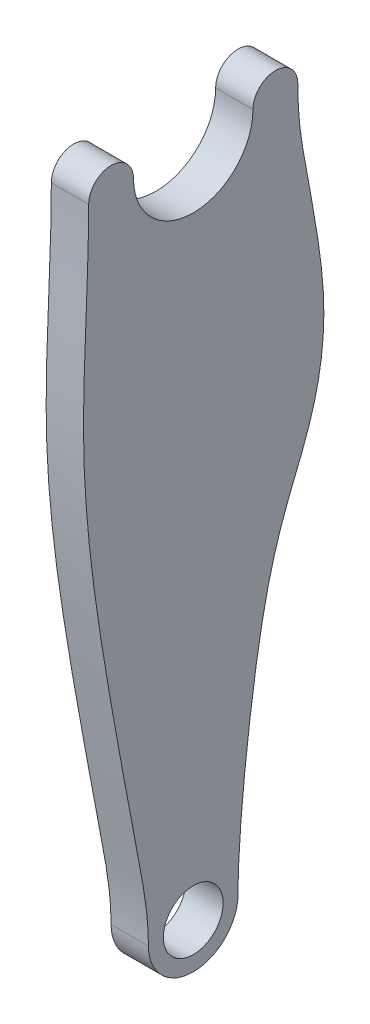
SolidWorks part; units mm, degrees
ref_plane "Front Plane" through (0, 0, 0) normal (0, 0, 1) x (1, 0, 0)
ref_plane "Top Plane" through (0, 0, 0) normal (0, 1, 0) x (1, 0, 0)
ref_plane "Right Plane" through (0, 0, 0) normal (1, 0, 0) x (0, 0, -1)
sketch "Sketch1" plane through (0, 0, 0) normal (1, 0, 0) x (0, 0, -1)
  line L0 (0, 0) -> (0, -180) construction
  line L1 (-22, 0) -> (0, 0) construction
  line L2 (0, 0) -> (22, 0) construction
  line L3 (-12, -180) -> (12, -180) construction
  line L4 (-28, 0) -> (-22, 0) construction
  line L5 (22, 0) -> (28, 0) construction
  arc A1 (-16, 0) -> (-28, 0) centre (-22, 0) ccw
  circle A2 centre (0, -180) radius 8
  arc A3 (12, -180) -> (-12, -180) centre (0, -180) cw
  arc A4 (-16, 0) -> (16, 0) centre (0, 0) ccw
  arc A5 (16, 0) -> (28, 0) centre (22, 0) cw
  spline S0 degree 3 poles (-28, 0) (-28, -19.8415) (-31.4918, -55.9451) (-24.0979, -109.0865) (-16.3697, -149.4261) (-12, -172.5449) (-12, -180) knots 0 0 0 0 0.318522 0.61075 0.87813 1 1 1 1
  spline S1 degree 3 poles (28, 0) (28, -7.1189) (29.32, -17.3743) (39.2187, -65.1846) (24.4894, -94.622) (16.8396, -123.056) (12, -165.4565) (12, -180) knots 0 0 0 0 0.084286 0.18761 0.382215 0.559767 0.781851 0.781851 0.781851 0.781851
  point P16 (-29.2937, -57.7324)
  point P19 (-23.443, -110.3884)
  point P21 (31.8122, -23.9167)
  point P23 (38.0942, -48.7713)
  point P24 (27.4422, -91.9254)
  point P25 (19.9312, -124.9738)
  point P26 (29.9003, -19.0004)
  point P28 (34.8166, -51.5025)
  point P29 (25.8034, -94.2469)
  point P30 (17.473, -125.52)
  dimension "D2" = 16
  dimension "D3" = 12
  dimension "D4" = 6
  dimension "D5" = 16
  dimension "D1" = 180
extrude "Boss-Extrude1" add sketch "Sketch1" along normal blind 10 contours S1 A5 A4 A1 S0 A3 A2
